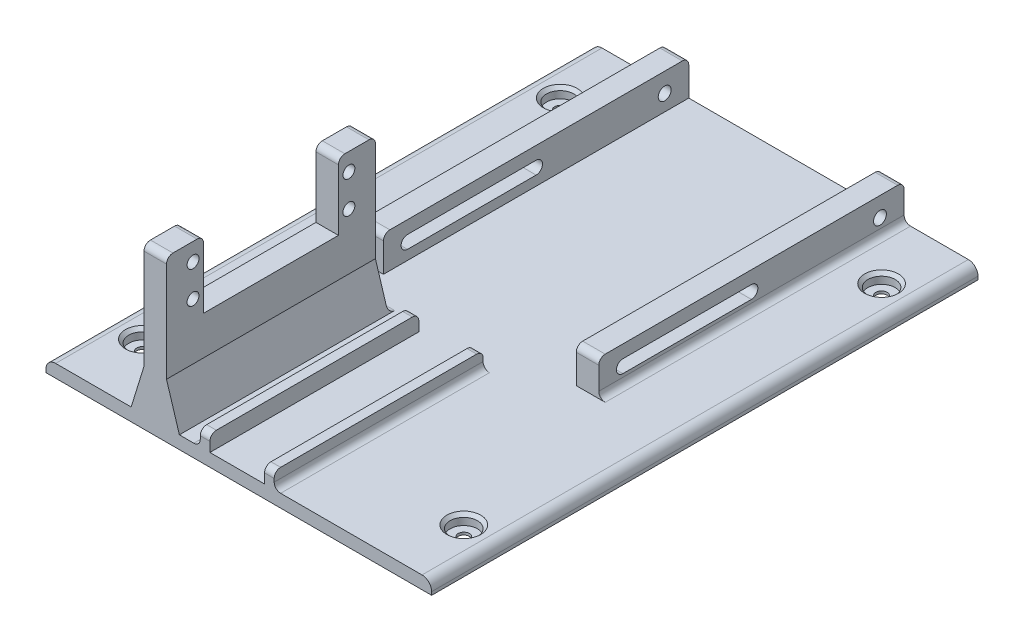
SolidWorks part; units mm, degrees
ref_plane "前视基准面" through (0, 0, 0) normal (0, 0, 1) x (1, 0, 0)
ref_plane "上视基准面" through (0, 0, 0) normal (0, 1, 0) x (1, 0, 0)
ref_plane "右视基准面" through (0, 0, 0) normal (1, 0, 0) x (0, 0, -1)
sketch "草图1" plane through (0, 0, 0) normal (0, 1, 0) x (1, 0, 0)
  line L1 (-57.3427, 85.9441) -> (62.6573, 85.9441)
  line L2 (-57.3427, 85.9441) -> (-57.3427, -84.0559)
  line L3 (-57.3427, -84.0559) -> (62.6573, -84.0559)
  line L4 (62.6573, 85.9441) -> (62.6573, -84.0559)
  dimension "D1" = 120
  dimension "D2" = 170
extrude "凸台-拉伸1" add sketch "草图1" along normal blind 4 contours L2 L3 L4 L1
sketch "草图2" plane through (0, 4, 0) normal (0, 1, 0) x (1, 0, 0)
  line L0 (2.6573, 95.957) -> (2.6573, -117.1596) construction
  line L1 (-68.2222, 0.9441) -> (80.3607, 0.9441) construction
  line L3 (-57.3427, 85.9441) -> (-57.3427, -84.0559) construction
  circle A0 centre (-47.3427, 65.9441) radius 1.75
  circle A1 centre (-47.3427, -64.0559) radius 1.75
  circle A2 centre (52.6573, -64.0559) radius 1.75
  circle A3 centre (52.6573, 65.9441) radius 1.75
  point P16 (2.6573, -10.6013)
  point P17 (-57.3427, 0.9441)
  dimension "D1" = 3.5
  dimension "D2" = 50
  dimension "D3" = 65
extrude "切除-拉伸1" cut sketch "草图2" against normal through all
sketch "草图3" plane through (0, 4, 0) normal (0, 1, 0) x (1, 0, 0)
  line L0 (-57.3427, 0.9441) -> (-70.0325, 0.9441)
  line L1 (2.6573, 96.5345) -> (2.6573, -95.869) construction
  line L2 (-34.3427, 85.9441) -> (-34.3427, -9.0559)
  line L3 (-57.3427, 85.9441) -> (62.6573, 85.9441) construction
  line L4 (-34.3427, -9.0559) -> (-27.3427, -9.0559)
  line L5 (-27.3427, -9.0559) -> (-27.3427, 85.9441)
  line L6 (-27.3427, 85.9441) -> (-34.3427, 85.9441)
  line L7 (39.6573, -9.0559) -> (32.6573, -9.0559)
  line L8 (32.6573, -9.0559) -> (32.6573, 85.9441)
  line L9 (32.6573, 85.9441) -> (39.6573, 85.9441)
  line L10 (39.6573, 85.9441) -> (39.6573, -9.0559)
  line L17 (-57.3427, 85.9441) -> (-57.3427, -84.0559) construction
  line L18 (-70.0325, 0.9441) -> (73.5501, 0.9441) construction
  line M14 (62.6573, 85.9441) -> (-57.3427, 85.9441)
  dimension "D1" = 7
  dimension "D2" = 30
  dimension "D3" = 95
extrude "凸台-拉伸2" add sketch "草图3" along normal blind 11 contours L4 L5 L2 M14 | L10 L8 L7 M14
sketch "草图4" plane through (-34.3427, 0, 0) normal (-1, 0, 0) x (0, 0, 1)
  line L0 (-96.1737, 9) -> (11.3823, 9) construction
  line L2 (9.0559, 15) -> (9.0559, 4) construction
  line L3 (-85.9441, 15) -> (-85.9441, 4) construction
  line L4 (-38.4441, 11) -> (1.5559, 11)
  line L5 (1.5559, 7) -> (-38.4441, 7)
  line L6 (-85.9441, 4) -> (9.0559, 4) construction
  circle A0 centre (-78.4441, 9) radius 2
  arc A1 (1.5559, 7) -> (1.5559, 11) centre (1.5559, 9) ccw
  arc A2 (-38.4441, 11) -> (-38.4441, 7) centre (-38.4441, 9) ccw
  dimension "D1" = 4
  dimension "D2" = 4
  dimension "D3" = 5
  dimension "D4" = 40
  dimension "D5" = 7.5
  dimension "D6" = 7.5
extrude "切除-拉伸3" cut sketch "草图4" against normal through all contours L5 A2 L4 A1 | A0
sketch "草图5" plane through (0, 4, 0) normal (0, 1, 0) x (1, 0, 0)
  line L0 (-57.3427, 0.9441) -> (62.6573, 0.9441) construction
  line L1 (-57.3427, 85.9441) -> (-57.3427, -84.0559) construction
  line L2 (62.6573, 85.9441) -> (62.6573, -84.0559) construction
  line L3 (2.6573, 85.9441) -> (2.6573, -84.0559) construction
  line L4 (-27.3427, 85.9441) -> (32.6573, 85.9441) construction
  line L5 (-57.3427, -84.0559) -> (62.6573, -84.0559) construction
  line L6 (-26.8427, -19.0559) -> (-19.8427, -19.0559)
  line L7 (-19.8427, -19.0559) -> (-19.8427, -84.0559)
  line L8 (-19.8427, -84.0559) -> (-26.8427, -84.0559)
  line L9 (-26.8427, -84.0559) -> (-26.8427, -19.0559)
  dimension "D1" = 22.5
  dimension "D2" = 7
  dimension "D3" = 65
extrude "凸台-拉伸3" add sketch "草图5" along normal blind 46
sketch "草图7" plane through (-26.8427, 0, 0) normal (-1, 0, 0) x (0, 0, 1)
  line L0 (51.5559, 50) -> (51.5559, 4) construction
  line L1 (19.0559, 50) -> (84.0559, 50) construction
  line L2 (19.0559, 4) -> (84.0559, 4) construction
  line L3 (72.5559, 50) -> (30.5559, 50)
  line L4 (30.5559, 50) -> (30.5559, 29)
  line L5 (30.5559, 29) -> (72.5559, 29)
  line L6 (30.5559, 39.5) -> (51.5559, 39.5) construction
  line L7 (72.5559, 50) -> (72.5559, 29)
  circle A1 centre (27.3059, 34.5) radius 1.85
  circle A2 centre (27.3059, 44.5) radius 1.85
  circle A3 centre (75.8059, 44.5) radius 1.85
  circle A4 centre (75.8059, 34.5) radius 1.85
  point P16 (51.5559, 29)
  dimension "D1" = 5
  dimension "D2" = 3.7
  dimension "D3" = 21
  dimension "D4" = 21
  dimension "D5" = 48.5
extrude "切除-拉伸4" cut sketch "草图7" against normal through all
sketch "草图9" plane through (0, 4, 0) normal (0, 1, 0) x (1, 0, 0)
  line L0 (-57.3427, 0.9441) -> (62.6573, 0.9441) construction
  line L1 (-57.3427, 85.9441) -> (-57.3427, -84.0559) construction
  line L2 (62.6573, 85.9441) -> (62.6573, -84.0559) construction
  line L3 (2.6573, 85.9441) -> (2.6573, -84.0559) construction
  line L4 (-27.3427, 85.9441) -> (32.6573, 85.9441) construction
  line L5 (-19.8427, -84.0559) -> (62.6573, -84.0559) construction
  line L6 (-9.3427, -19.0559) -> (-6.3427, -19.0559)
  line L7 (-6.3427, -19.0559) -> (-6.3427, -84.0559)
  line L8 (-6.3427, -84.0559) -> (-9.3427, -84.0559)
  line L9 (-9.3427, -84.0559) -> (-9.3427, -19.0559)
  line L10 (-19.8427, -19.0559) -> (-26.8427, -19.0559) construction
  line L11 (10.6573, -84.0559) -> (13.6573, -84.0559)
  line L12 (10.6573, -19.0559) -> (10.6573, -84.0559)
  line L13 (13.6573, -19.0559) -> (10.6573, -19.0559)
  line L14 (13.6573, -84.0559) -> (13.6573, -19.0559)
  point P22 (0, 0)
  point P23 (11.2383, -84.0559)
  dimension "D1" = 9
  dimension "D2" = 3
  dimension "D3" = 3
  dimension "D4" = 65
  dimension "D5" = 8
extrude "凸台-拉伸4" add sketch "草图9" along normal blind 5
ref_plane "基准面2" through (-26.8427, 4, 84.0559) normal (0, 0, 1) x (1, 0, 0)
sketch "草图11" plane through (-26.8427, 4, 84.0559) normal (0, 0, 1) x (1, 0, 0)
  line L0 (0, 12.9765) -> (-4, 0)
  line L1 (0, 46) -> (0, 0) construction
  line L2 (-7.5, 0) -> (-0.5, 0) construction
  line L3 (0, 12.9765) -> (0, 0)
  line L4 (0, 0) -> (-4, 0)
  line L5 (3.5, 46) -> (3.5, -4) construction
  line L6 (0, 46) -> (7, 46) construction
  line L7 (-30.5, -4) -> (89.5, -4) construction
  line L8 (7, 0) -> (11, 0)
  line L9 (7, 12.9765) -> (7, 0)
  line L10 (7, 12.9765) -> (11, 0)
extrude "凸台-拉伸5" add sketch "草图11" against normal blind 65
sketch "草图13" plane through (0, 4, 0) normal (0, 1, 0) x (1, 0, 0)
  line L0 (-57.3427, 0.9441) -> (62.6573, 0.9441) construction
  line L1 (-57.3427, 85.9441) -> (-57.3427, -84.0559) construction
  line L2 (62.6573, 85.9441) -> (62.6573, -84.0559) construction
  line L3 (2.6573, 85.9441) -> (2.6573, -84.0559) construction
  line L4 (-27.3427, 85.9441) -> (32.6573, 85.9441) construction
  line L5 (-81.8427, -84.0559) -> (28.1573, -84.0559) construction
  circle A0 centre (-47.3427, 65.9441) radius 4.25
  circle A1 centre (52.6573, 65.9441) radius 4.25
  circle A2 centre (52.6573, -64.0559) radius 4.25
  circle A3 centre (-47.3427, -64.0559) radius 4.25
  dimension "D1" = 8.5
extrude "切除-拉伸5" cut sketch "草图13" against normal blind 3.2
fillet "圆角3" radius 3 2 edges at (-57.3427, 4, -0.9441) (62.6573, 4, -0.9441)
fillet "圆角5" radius 2 2 edges at (-9.3427, 4, 51.5559) (13.6573, 4, 51.5559)
chamfer "倒角1" distance 1 angle 45 4 edges at (52.6573, 4, -70.1941) (52.6573, 4, 68.3059) (-47.3427, 4, 59.8059) (-47.3427, 4, -61.6941)
fillet "圆角6" radius 2 15 edges at (-30.8427, 15, 9.0559) (-30.8427, 15, -85.9441) (36.1573, 15, -85.9441) (36.1573, 15, 9.0559) (-34.3427, 4, -38.4441) (39.6573, 4, -38.4441) (-23.3427, 50, 84.0559) (-23.3427, 50, 72.5559) (-23.3427, 50, 30.5559) (-23.3427, 50, 19.0559) (-23.3427, 4, 19.0559) (-7.8427, 9, 84.0559) (12.1573, 9, 84.0559) (12.1573, 9, 19.0559) (-7.8427, 9, 19.0559)
